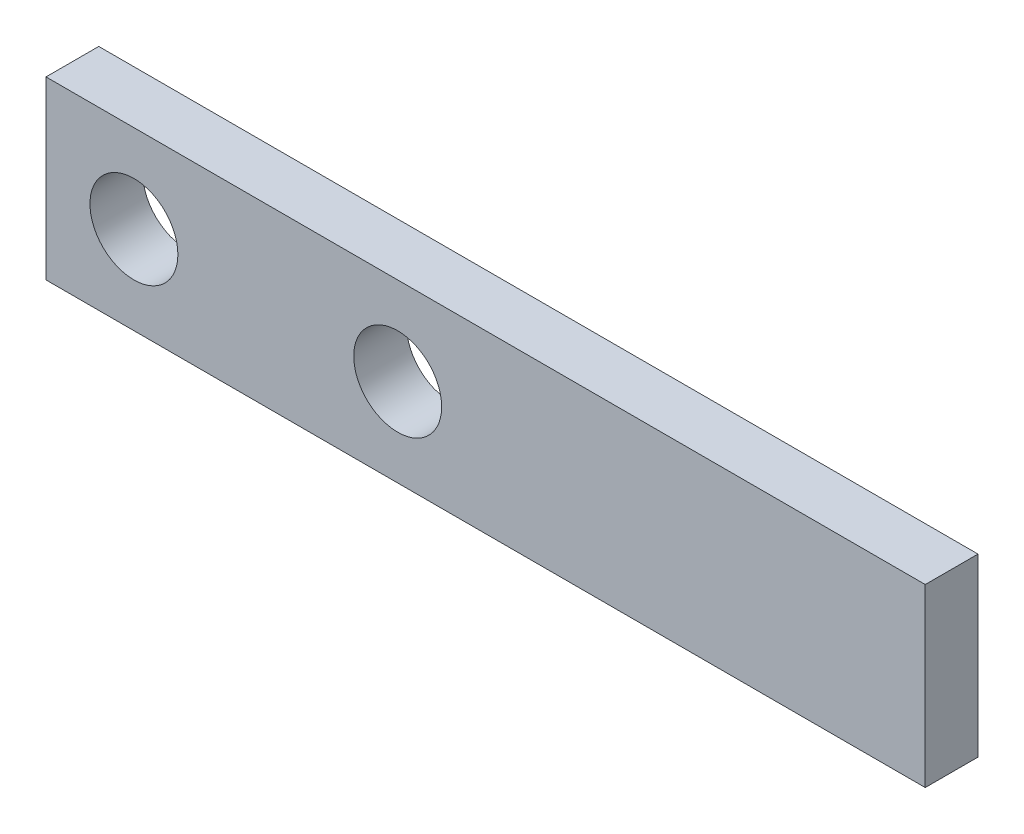
SolidWorks part; units mm, degrees
ref_plane "前基準面" through (0, 0, 0) normal (0, 0, 1) x (1, 0, 0)
ref_plane "上基準面" through (0, 0, 0) normal (0, 1, 0) x (1, 0, 0)
ref_plane "右基準面" through (0, 0, 0) normal (1, 0, 0) x (0, 0, -1)
sketch "草圖1" plane through (0, 0, 0) normal (0, 0, 1) x (1, 0, 0)
  line L0 (-25, 0) -> (25, 0) construction
  line L1 (-25, -5) -> (25, -5)
  line L2 (-25, -5) -> (-25, 5)
  line L3 (-25, 5) -> (25, 5)
  line L4 (25, -5) -> (25, 5)
  line L5 (-25, -5) -> (25, 5) construction
  line L6 (-25, 5) -> (25, -5) construction
  circle A0 centre (-20, 0) radius 2.5
  circle A1 centre (-5, 0) radius 2.5
  point P0 (0, 0)
  dimension "D3" = 5
  dimension "D4" = 5
  dimension "D1" = 50
  dimension "D2" = 10
  dimension "D5" = 5
  dimension "D6" = 15
extrude "填料-伸長1" add sketch "草圖1" along normal blind 3
